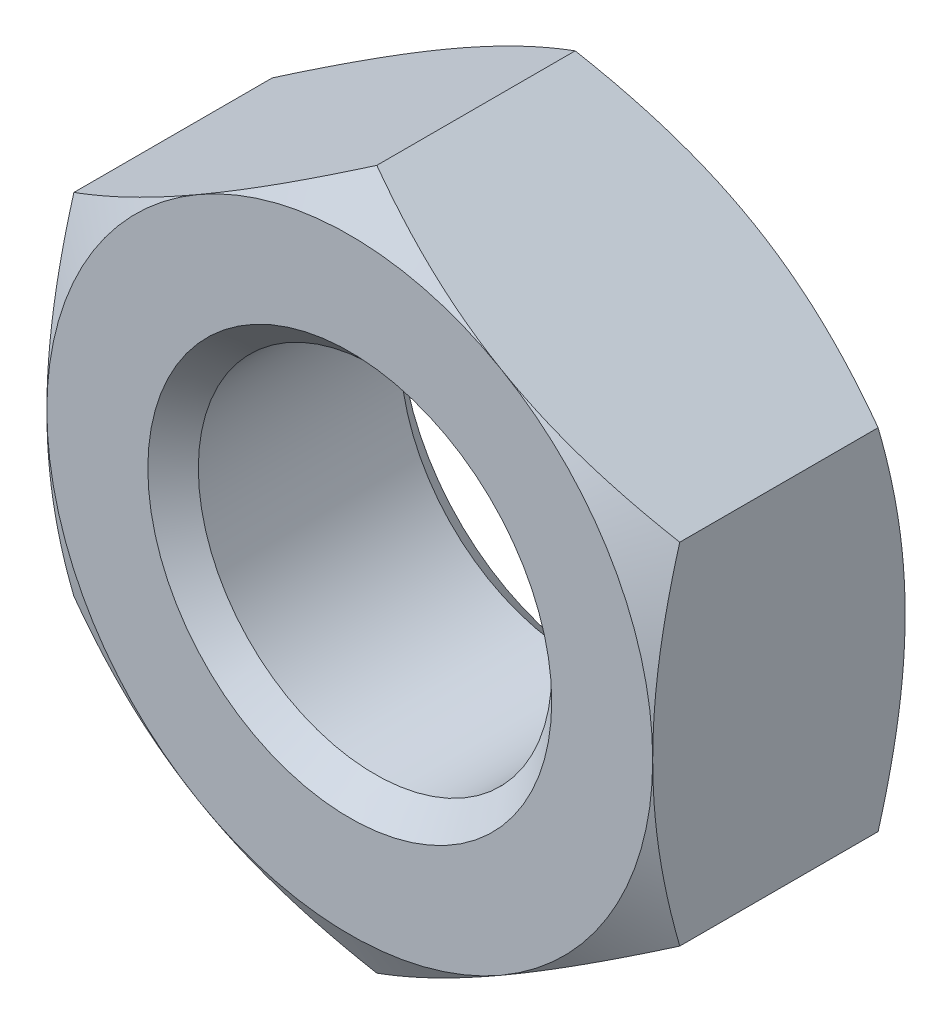
SolidWorks part; units mm, degrees
ref_plane "Front Plane" through (0, 0, 0) normal (0, 0, 1) x (1, 0, 0)
ref_plane "Top Plane" through (0, 0, 0) normal (0, 1, 0) x (1, 0, 0)
ref_plane "Right Plane" through (0, 0, 0) normal (1, 0, 0) x (0, 0, -1)
sketch "Sketch1" plane through (0, 0, 0) normal (0, 0, 1) x (1, 0, 0)
  line L1 (12, -6.9282) -> (12, 6.9282)
  line L2 (12, 6.9282) -> (0, 13.8564)
  line L3 (0, 13.8564) -> (-12, 6.9282)
  line L4 (-12, 6.9282) -> (-12, -6.9282)
  line L5 (-12, -6.9282) -> (0, -13.8564)
  line L6 (0, -13.8564) -> (12, -6.9282)
  circle A0 centre (0, 0) radius 12 construction
  dimension "D1" = 24
extrude "Boss-Extrude2" add sketch "Sketch1" along normal blind 10
sketch "Sketch2" plane through (0, 0, 10) normal (0, 0, 1) x (1, 0, 0)
  circle A0 centre (0, 0) radius 7
  dimension "D1" = 14
extrude "Cut-Extrude1" cut sketch "Sketch2" against normal through all
sketch "Sketch3" plane through (0, 0, 10) normal (0, 0, 1) x (1, 0, 0)
  circle A0 centre (0, 0) radius 12
extrude "Cut-Extrude2" cut sketch "Sketch3" against normal blind 10 draft 60 flip side to cut
sketch "Sketch4" plane through (0, 0, 0) normal (0, 0, -1) x (-1, 0, 0)
  circle A0 centre (0, 0) radius 12
extrude "Cut-Extrude3" cut sketch "Sketch4" against normal blind 10 draft 60 flip side to cut
chamfer "Chamfer1" distance 1 angle 45 2 edges at (7, 0, 10) (7, 0, 0)
